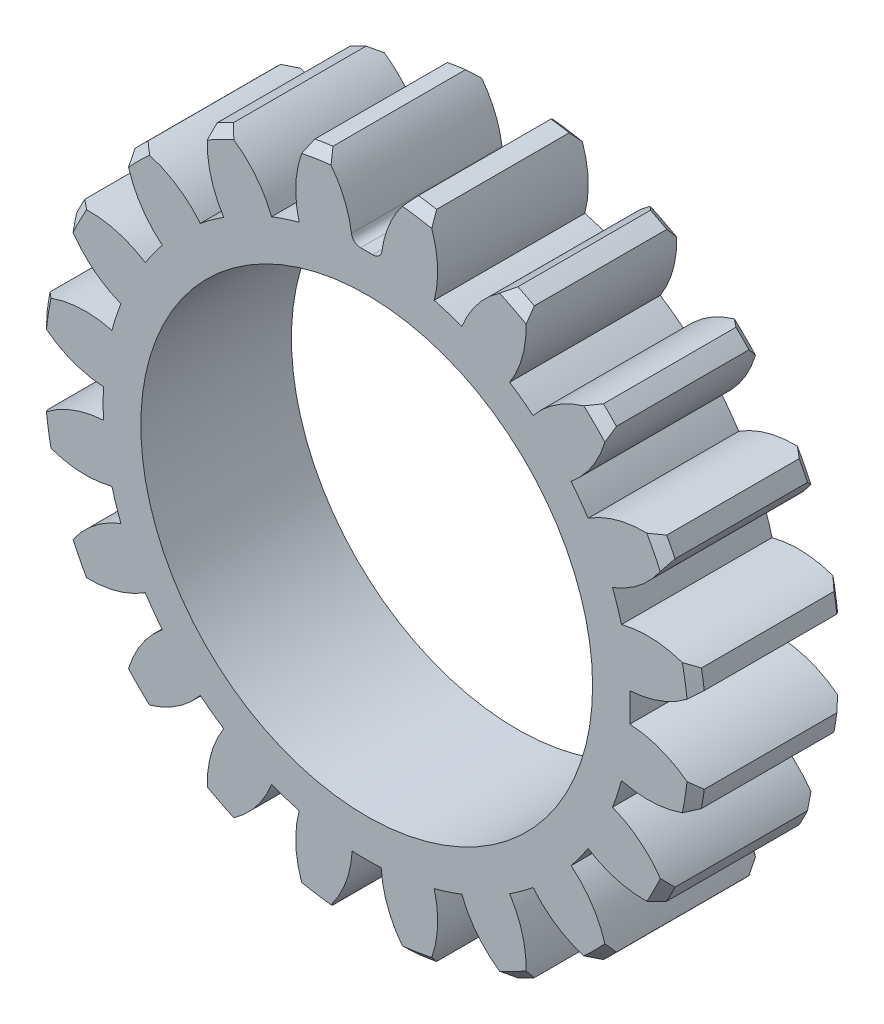
SolidWorks part; units mm, degrees
ref_plane "Front Plane" through (0, 0, 0) normal (0, 0, 1) x (1, 0, 0)
ref_plane "Top Plane" through (0, 0, 0) normal (0, 1, 0) x (1, 0, 0)
ref_plane "Right Plane" through (0, 0, 0) normal (1, 0, 0) x (0, 0, -1)
sketch "Sketch1" plane through (0, 0, 0) normal (0, 0, 1) x (1, 0, 0)
  circle A0 centre (0, 0) radius 17.5
  circle A1 centre (0, 0) radius 20
  circle A2 centre (0, 0) radius 22
  dimension "D1" = 35
  dimension "D2" = 40
  dimension "D3" = 44
extrude "Boss-Extrude1" add sketch "Sketch1" along normal blind 10 contours A2
sketch "Sketch2" plane through (0, 0, 10) normal (0, 0, 1) x (1, 0, 0)
  line L0 (0, -24.8645) -> (0, 25.8556) construction
  line L1 (-0.9626, 17.4735) -> (0, 0) construction
  line L2 (0.9626, 17.4735) -> (0, 0) construction
  line L3 (-1.5692, 19.9383) -> (1.5692, 19.9383) construction
  line L4 (-2.5781, 22.1523) -> (0.6741, 15.0159) construction
  line L5 (-1.5692, 19.9383) -> (7.9112, 24.2588) construction
  line L6 (-1.5692, 19.9383) -> (11.1775, 20.9415) construction
  line L7 (0, 0) -> (3.4416, 21.7291) construction
  line L8 (1.5692, 19.9383) -> (4.6689, 19.4474) construction
  arc A0 (-0.9626, 17.4735) -> (-2.8367, 21.8164) centre (-7.8048, 17.0966) ccw
  circle A1 centre (0, 0) radius 17.5 construction
  circle A2 centre (0, 0) radius 22 construction
  arc A3 (0.9626, 17.4735) -> (2.8367, 21.8164) centre (7.8048, 17.0966) cw
  circle A4 centre (0, 0) radius 20 construction
  arc A5 (0.9626, 17.4735) -> (-0.9626, 17.4735) centre (0, 0) ccw
  arc A7 (2.8367, 21.8164) -> (-2.8367, 21.8164) centre (0, 0) ccw
  dimension "D1" = 20
  dimension "D2" = 9
extrude "Cut-Extrude1" cut sketch "Sketch2" against normal blind 10
fillet "Fillet1" radius 0.6 2 edges at (0.9626, 17.4735, 5) (-0.9626, 17.4735, 5)
chamfer "Chamfer1" distance 0.6 angle 45 2 edges at (0, -22, 0) (0, -22, 10)
pattern_circular "CirPattern1" count 20 over 360 about axis through (0, 0, 0) along (0, 0, 1) of "Cut-Extrude1"
sketch "Sketch3" plane through (0, 0, 10) normal (0, 0, 1) x (1, 0, 0)
  circle A0 centre (0, 0) radius 15
  dimension "D1" = 30
extrude "Cut-Extrude2" cut sketch "Sketch3" against normal blind 10
equation "\"module\"= 2mm"
equation "\"number of teeth\"= 20"
equation "\"pressure angle\"= 20"
equation "\"add\"= \"module\""
equation "\"ded\"= \"module\" * 1.25"
equation "\"pitch d\"= \"number of teeth\" * \"module\""
equation "\"outside d\"= \"pitch d\" + 2 * \"add\""
equation "\"root d\"= \"pitch d\" - 2 * \"ded\""
equation "\"D1@Fillet1\"=0.3*\"module\""
equation "\"D1@Chamfer1\"=\"module\"*0.3"
